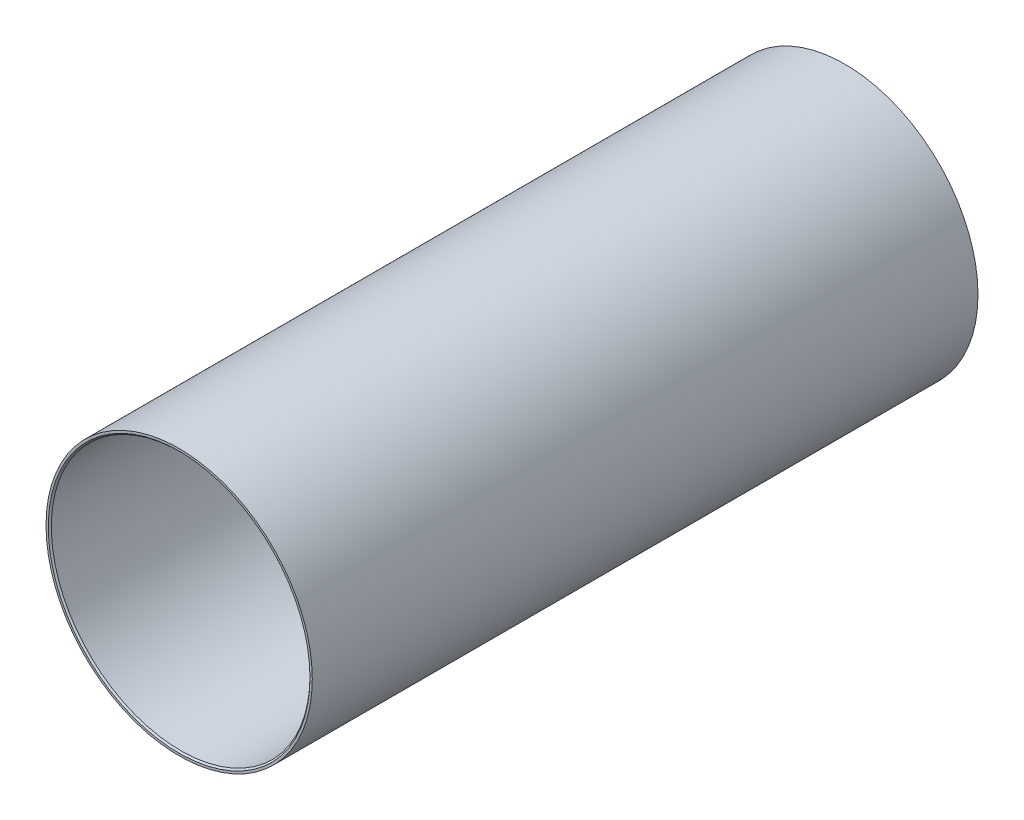
SolidWorks part; units mm, degrees
ref_plane "Front Plane" through (0, 0, 0) normal (0, 0, 1) x (1, 0, 0)
ref_plane "Top Plane" through (0, 0, 0) normal (0, 1, 0) x (1, 0, 0)
ref_plane "Right Plane" through (0, 0, 0) normal (1, 0, 0) x (0, 0, -1)
sketch "Sketch2" plane through (0, 0, 0) normal (0, 0, 1) x (1, 0, 0)
  circle A0 centre (0, 0) radius 17.5
  circle A1 centre (0, 0) radius 17
  dimension "D1" = 35
  dimension "D2" = 34
extrude "Boss-Extrude1" add sketch "Sketch2" along normal blind 87.5
chamfer "Chamfer1" distance 0.2 angle 45 2 edges at (17, 0, 0) (17, 0, 87.5)
